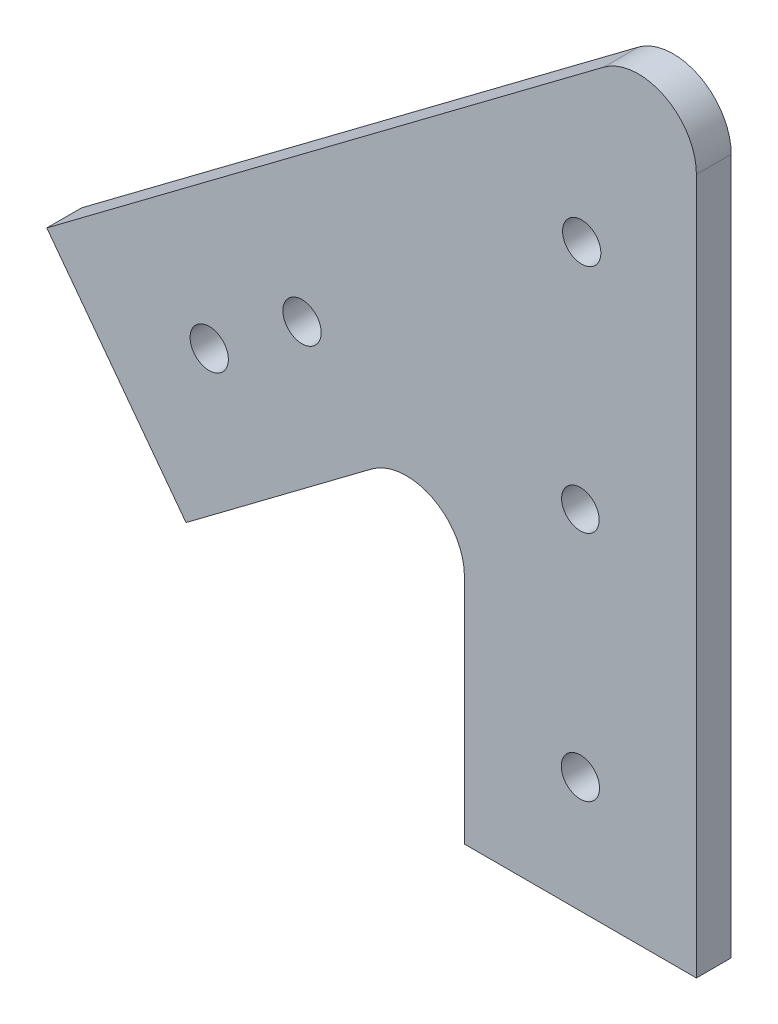
SolidWorks part; units mm, degrees
ref_plane "前视基准面" through (0, 0, 0) normal (0, 0, 1) x (1, 0, 0)
ref_plane "上视基准面" through (0, 0, 0) normal (0, 1, 0) x (1, 0, 0)
ref_plane "右视基准面" through (0, 0, 0) normal (1, 0, 0) x (0, 0, -1)
other "Configuration Table"
sketch "草图1" plane through (0, 0, 0) normal (0, 0, 1) x (1, 0, 0)
  line L0 (-28.3859, -7.359) -> (-16.3859, -23.359)
  line L1 (-16.3859, -23.359) -> (7.6141, -5.359)
  line L2 (27.6109, -35.3583) -> (27.6113, 34.6389)
  line L3 (7.6111, -5.3613) -> (7.6109, -35.3583)
  line L4 (7.6141, -5.359) -> (7.6109, -35.3583)
  line L5 (7.6109, -35.3583) -> (27.6109, -35.3583)
  line L6 (-28.3859, -7.359) -> (-4.3859, 10.641)
  line L7 (-4.3859, 10.641) -> (27.6113, 34.6389)
  line L8 (7.6109, -35.3583) -> (27.6109, -35.3583)
  line L9 (-14.3859, -9.359) -> (17.7248, 14.6417) construction
  line L10 (17.7248, 14.6417) -> (17.611, -25.3583) construction
  circle A0 centre (-14.3859, -9.359) radius 1.65
  circle A1 centre (-6.3859, -3.359) radius 1.65
  circle A2 centre (17.611, -25.3583) radius 1.65
  circle A3 centre (17.611, -5.3583) radius 1.6203
  circle A4 centre (17.7248, 14.6417) radius 1.65
  dimension "D1" = 3.3
  dimension "D4" = 3.3
  dimension "D2" = 10
  dimension "D3" = 20
  dimension "D5" = 20
  dimension "D6" = 10
extrude "凸台-拉伸1" add sketch "草图1" along normal blind 3 contours L7 L6 L0 L1 L4 L5 L2 A4 A3 A2 A1 A0
fillet "圆角1" radius 5 2 edges at (27.6113, 34.6389, 1.5) (7.6141, -5.359, 1.5)
